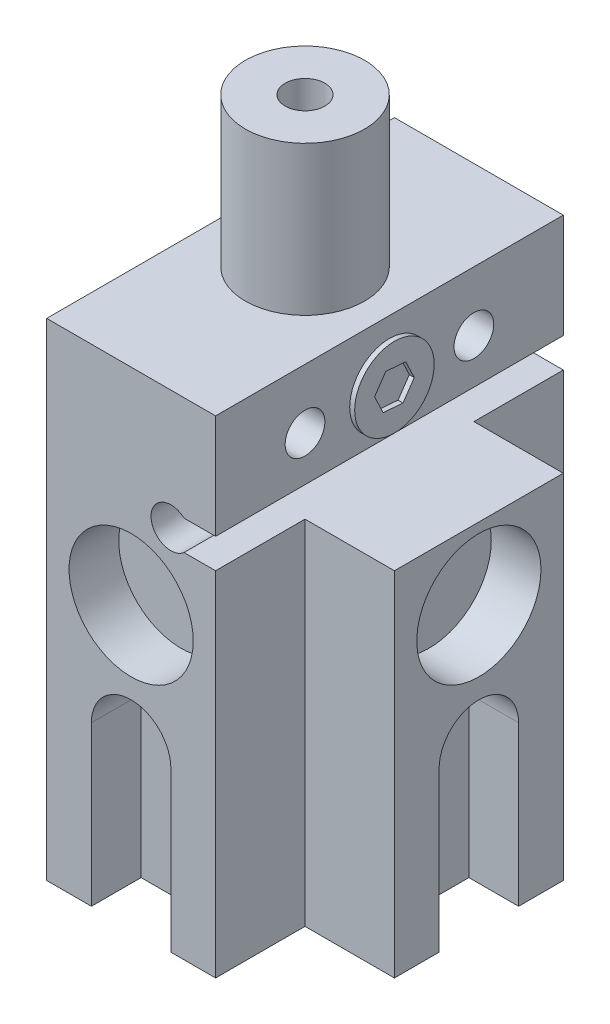
SolidWorks part; units mm, degrees
material "1060 Alloy"
ref_plane "Front Plane" through (0, 0, 0) normal (0, 0, 1) x (1, 0, 0)
ref_plane "Top Plane" through (0, 0, 0) normal (0, 1, 0) x (1, 0, 0)
ref_plane "Right Plane" through (0, 0, 0) normal (1, 0, 0) x (0, 0, -1)
sketch "Sketch1" plane through (0, 0, 0) normal (1, 0, 0) x (0, 0, -1)
  line L1 (0, 0) -> (35, 0)
  line L2 (0, 0) -> (0, 49)
  line L3 (0, 49) -> (35, 49)
  line L4 (35, 0) -> (35, 49)
  dimension "D1" = 35
  dimension "D2" = 49
extrude "Boss-Extrude1" add sketch "Sketch1" along normal blind 17
sketch "Sketch2" plane through (17, 0, 0) normal (1, 0, 0) x (0, 0, -1)
  line L0 (35, 43) -> (26, 43) construction
  line L1 (35, 0) -> (35, 49) construction
  line L2 (26, 43) -> (26, 49) construction
  line L3 (35, 49) -> (0, 49) construction
  line L4 (0, 43) -> (9, 43) construction
  line L5 (0, 49) -> (0, 0) construction
  line L6 (9, 43) -> (9, 49) construction
  circle A0 centre (9, 43) radius 2
  circle A1 centre (26, 43) radius 2
  dimension "D4" = 4
  dimension "D5" = 4
  dimension "D1" = 9
  dimension "D2" = 6
  dimension "D3" = 9
extrude "Cut-Extrude1" cut sketch "Sketch2" against normal blind 37
sketch "Sketch3" plane through (17, 0, 0) normal (1, 0, 0) x (0, 0, -1)
  line L0 (0, 0) -> (35, 0) construction
  line L1 (26, 0) -> (9, 0)
  line L2 (26, 0) -> (26, 35.5)
  line L3 (26, 35.5) -> (9, 35.5)
  line L4 (9, 0) -> (9, 35.5)
  line L5 (35, 0) -> (35, 49) construction
  dimension "D1" = 35.5
  dimension "D2" = 17
  dimension "D3" = 9
extrude "Boss-Extrude2" add sketch "Sketch3" along normal blind 9
sketch "Sketch4" plane through (0, 0, 0) normal (-1, 0, 0) x (0, 0, 1)
  line L0 (0, 0) -> (-35, 0) construction
  line L1 (-9, 0) -> (-26, 0)
  line L2 (-9, 0) -> (-9, 35.5)
  line L3 (-9, 35.5) -> (-26, 35.5)
  line L4 (-26, 0) -> (-26, 35.5)
  line L5 (-35, 0) -> (-35, 49) construction
  dimension "D1" = 17
  dimension "D2" = 9
  dimension "D3" = 35.5
extrude "Boss-Extrude3" add sketch "Sketch4" along normal blind 9
sketch "Sketch5" plane through (0, 0, 0) normal (0, 0, 1) x (1, 0, 0)
  line L0 (17, 49) -> (17, 0) construction
  line L1 (17, 35.5) -> (13.8229, 35.5)
  line L2 (17, 35.5) -> (17, 38.5)
  line L3 (17, 38.5) -> (13.8229, 38.5)
  line L5 (17, 0) -> (0, 0) construction
  arc A0 (13.8229, 38.5) -> (13.8229, 35.5) centre (12.5, 37) ccw
  dimension "D4" = 4
  dimension "D5" = 4.5
  dimension "D2" = 35.5
  dimension "D3" = 3
extrude "Cut-Extrude2" cut sketch "Sketch5" against normal blind 59
sketch "Sketch6" plane through (26, 0, 0) normal (1, 0, 0) x (0, 0, -1)
  line L0 (26, 35.5) -> (9, 35.5) construction
  line L1 (26, 0) -> (26, 35.5) construction
  circle A0 centre (17.5, 28.25) radius 6.25
  dimension "D1" = 12.5
  dimension "D2" = 7.25
  dimension "D3" = 8.5
extrude "Cut-Extrude3" cut sketch "Sketch6" against normal blind 5
sketch "Sketch7" plane through (-9, 0, 0) normal (-1, 0, 0) x (0, 0, 1)
  line L0 (-9, 0) -> (-9, 35.5) construction
  line L1 (-9, 35.5) -> (-26, 35.5) construction
  circle A0 centre (-17.5, 28.25) radius 6.25
  dimension "D1" = 12.5
  dimension "D2" = 8.5
  dimension "D3" = 7.25
extrude "Cut-Extrude4" cut sketch "Sketch7" against normal blind 5
sketch "Sketch8" plane through (0, 0, -35) normal (0, 0, -1) x (-1, 0, 0)
  line L0 (-13.8229, 35.5) -> (-17, 35.5) construction
  line L1 (0, 0) -> (0, 49) construction
  circle A0 centre (-8.5, 28.25) radius 6.25
  point P4 (-15.4114, 35.5)
  dimension "D1" = 12.5
  dimension "D2" = 7.25
  dimension "D3" = 8.5
extrude "Cut-Extrude5" cut sketch "Sketch8" against normal blind 5
sketch "Sketch9" plane through (0, 0, 0) normal (0, 0, 1) x (1, 0, 0)
  line L0 (13.8229, 35.5) -> (17, 35.5) construction
  line L1 (17, 35.5) -> (17, 0) construction
  circle A0 centre (8.5, 28.25) radius 6.25
  dimension "D1" = 12.5
  dimension "D2" = 7.25
  dimension "D3" = 8.5
extrude "Cut-Extrude6" cut sketch "Sketch9" against normal blind 5
sketch "Sketch10" plane through (17, 0, 0) normal (1, 0, 0) x (0, 0, -1)
  line L0 (9, 43) -> (26, 43) construction
  line L2 (18.6366, 44.6532) -> (16.6366, 44.8109)
  line L3 (16.6366, 44.8109) -> (15.5, 43.1577)
  line L4 (15.5, 43.1577) -> (16.3634, 41.3468)
  line L5 (16.3634, 41.3468) -> (18.3634, 41.1891)
  line L6 (18.3634, 41.1891) -> (19.5, 42.8423)
  line L7 (19.5, 42.8423) -> (18.6366, 44.6532)
  circle A1 centre (17.5, 43) radius 4
  circle A2 centre (17.5, 43) radius 1.7374 construction
  point P6 (17.5, 43)
  dimension "D1" = 8
  dimension "D2" = 4
extrude "Boss-Extrude4" add sketch "Sketch10" along normal blind 0.5
sketch "Sketch11" plane through (26, 0, 0) normal (1, 0, 0) x (0, 0, -1)
  line L0 (9, 0) -> (26, 0) construction
  line L1 (13.5, 0) -> (21.5, 0)
  line L2 (13.5, 0) -> (13.5, 16)
  line L4 (21.5, 0) -> (21.5, 16)
  line L5 (26, 0) -> (26, 35.5) construction
  arc A0 (21.5, 16) -> (13.5, 16) centre (17.5, 16) ccw
  dimension "D1" = 8
  dimension "D2" = 4.5
extrude "Cut-Extrude7" cut sketch "Sketch11" against normal blind 5
sketch "Sketch12" plane through (-9, 0, 0) normal (-1, 0, 0) x (0, 0, 1)
  line L0 (-26, 0) -> (-9, 0) construction
  line L1 (-21.5, 0) -> (-13.5, 0)
  line L2 (-21.5, 0) -> (-21.5, 16)
  line L4 (-13.5, 0) -> (-13.5, 16)
  line L5 (-9, 0) -> (-9, 35.5) construction
  arc A0 (-13.5, 16) -> (-21.5, 16) centre (-17.5, 16) ccw
  dimension "D1" = 4.5
  dimension "D2" = 8
  dimension "D3" = 16
extrude "Cut-Extrude8" cut sketch "Sketch12" against normal blind 5
sketch "Sketch13" plane through (0, 0, -35) normal (0, 0, -1) x (-1, 0, 0)
  line L0 (-17, 0) -> (0, 0) construction
  line L1 (-12.5, 0) -> (-4.5, 0)
  line L2 (-12.5, 0) -> (-12.5, 16)
  line L4 (-4.5, 0) -> (-4.5, 16)
  line L5 (0, 0) -> (0, 49) construction
  arc A0 (-4.5, 16) -> (-12.5, 16) centre (-8.5, 16) ccw
  dimension "D1" = 8
  dimension "D2" = 4.5
  dimension "D3" = 16
extrude "Cut-Extrude9" cut sketch "Sketch13" against normal blind 5
sketch "Sketch14" plane through (0, 0, 0) normal (0, 0, 1) x (1, 0, 0)
  line L0 (17, 0) -> (0, 0) construction
  line L1 (4.5, 0) -> (12.5, 0)
  line L2 (4.5, 0) -> (4.5, 16)
  line L4 (12.5, 0) -> (12.5, 16)
  line L5 (17, 35.5) -> (17, 0) construction
  arc A0 (12.5, 16) -> (4.5, 16) centre (8.5, 16) ccw
  dimension "D1" = 8
  dimension "D2" = 4.5
  dimension "D3" = 16
extrude "Cut-Extrude10" cut sketch "Sketch14" against normal blind 5
sketch "Sketch15" plane through (0, 49, 0) normal (0, 1, 0) x (1, 0, 0)
  line L0 (0, 35) -> (17, 0) construction
  circle A0 centre (8.5, 17.5) radius 6
  dimension "D1" = 12
extrude "Boss-Extrude5" add sketch "Sketch15" along normal blind 15
sketch "Sketch19" plane through (0, 64, 0) normal (0, 1, 0) x (1, 0, 0)
  circle A0 centre (8.5, 17.5) radius 2
  dimension "D1" = 4
extrude "Cut-Extrude11" cut sketch "Sketch19" against normal blind 24
